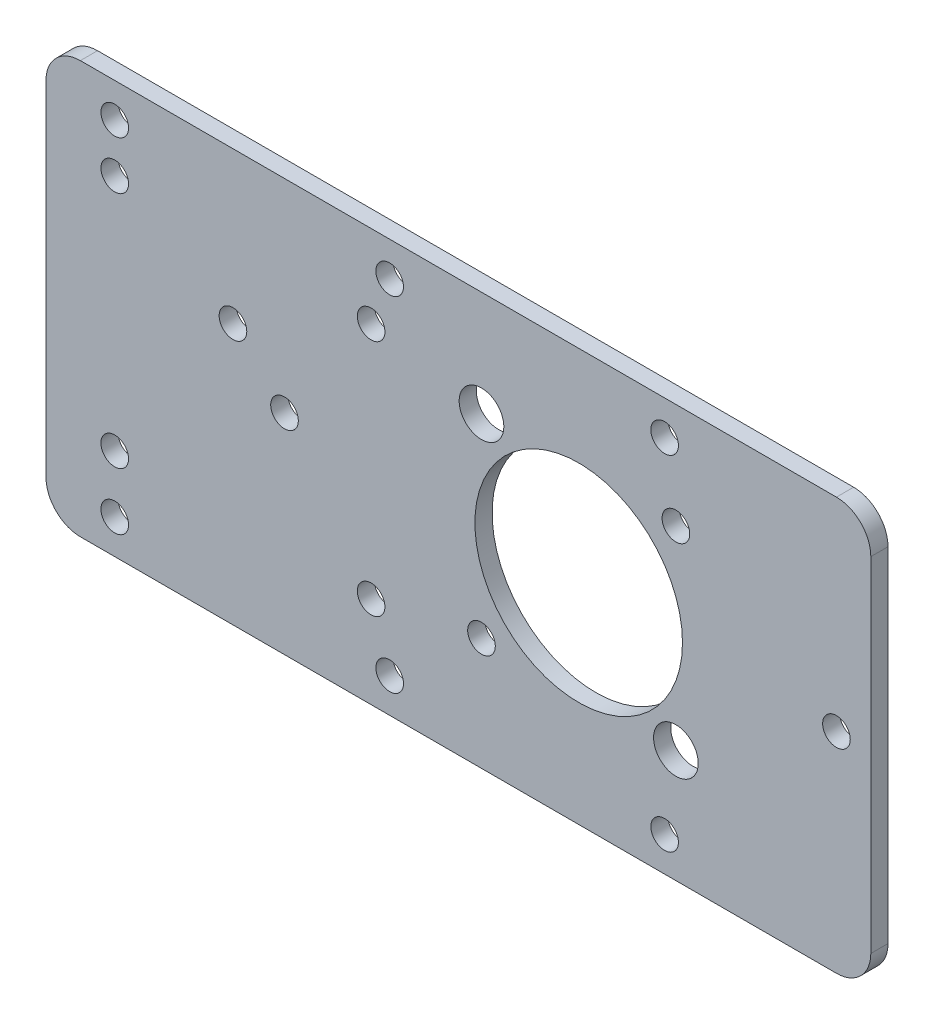
SolidWorks part; units mm, degrees
ref_plane "Front Plane" through (0, 0, 0) normal (0, 0, 1) x (1, 0, 0)
ref_plane "Top Plane" through (0, 0, 0) normal (0, 1, 0) x (1, 0, 0)
ref_plane "Right Plane" through (0, 0, 0) normal (1, 0, 0) x (0, 0, -1)
sketch "Sketch1" plane through (0, 0, 0) normal (0, 0, 1) x (1, 0, 0)
  line L1 (-24.7695, 9.8597) -> (-24.7695, 73.3597)
  line L2 (127.6305, 73.3597) -> (127.6305, 9.8597)
  line L6 (-18.4195, 79.7097) -> (121.2805, 79.7097)
  line L7 (-18.4195, 3.5097) -> (121.2805, 3.5097)
  circle A0 centre (89.5305, 9.8597) radius 2.5527
  circle A1 centre (89.5305, 73.3597) radius 2.5527
  circle A2 centre (-12.0695, 73.3597) radius 2.5527
  arc A3 (-24.7695, 73.3597) -> (-18.4195, 79.7097) centre (-18.4195, 73.3597) cw
  arc A4 (-24.7695, 9.8597) -> (-18.4195, 3.5097) centre (-18.4195, 9.8597) ccw
  arc A5 (121.2805, 3.5097) -> (127.6305, 9.8597) centre (121.2805, 9.8597) ccw
  arc A6 (121.2805, 79.7097) -> (127.6305, 73.3597) centre (121.2805, 73.3597) cw
  circle A9 centre (-12.0695, 64.4274) radius 2.5527
  circle A13 centre (38.7305, 73.3597) radius 2.5527
  circle A14 centre (35.3015, 64.4274) radius 2.5527
  circle A15 centre (9.7742, 51.7274) radius 2.5527
  circle A16 centre (19.2992, 42.2024) radius 2.5527
  circle A18 centre (-12.0695, 20.4337) radius 2.5527
  circle A23 centre (35.3015, 20.4337) radius 2.5527
  circle A24 centre (38.7305, 9.8597) radius 2.5527
  circle A25 centre (55.695, 24.3332) radius 2.5527
  circle A26 centre (55.695, 60.2542) radius 4.1275
  circle A27 centre (91.6161, 60.2542) radius 2.5527
  circle A29 centre (91.6161, 24.3332) radius 4.1275
  circle A30 centre (73.6555, 42.2024) radius 19.177
  circle A31 centre (-12.0695, 9.8597) radius 2.5527
  circle A32 centre (121.2805, 42.2024) radius 2.5527
  point P11 (0, 0)
  dimension "D3" = 6.35
  dimension "D4" = 5.1054
  dimension "D22" = 8.255
  dimension "D23" = 38.354
  dimension "D1" = 152.4
  dimension "D2" = 76.2
  dimension "D6" = 50.8
  dimension "D7" = 35.921
  dimension "D8" = 35.921
  dimension "D9" = 17.9605
  dimension "D10" = 18.0518
  dimension "D11" = 43.9937
  dimension "D12" = 47.371
  dimension "D13" = 25.5273
  dimension "D14" = 12.7
  dimension "D15" = 9.525
  dimension "D16" = 9.525
  dimension "D5" = 50.8
  dimension "D19" = 63.5
  dimension "D20" = 12.7
  dimension "D21" = 6.35
  dimension "D24" = 12.7
  dimension "D25" = 16.9239
  dimension "D26" = 6.35
  dimension "D17" = 67.7645
  dimension "D18" = 3.8995
extrude "Boss-Extrude1" add sketch "Sketch1" along normal blind 3.175
equation "\"D12@Sketch1\"=1.664+0.201"
